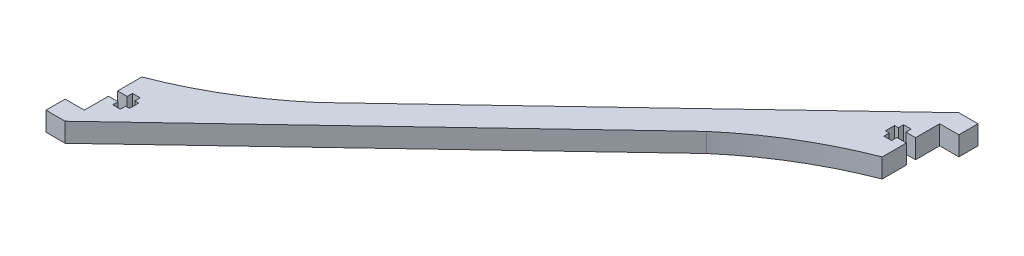
SolidWorks part; units mm, degrees
material "6061 Alloy"
ref_plane "Front Plane" through (0, 0, 0) normal (0, 0, 1) x (1, 0, 0)
ref_plane "Top Plane" through (0, 0, 0) normal (0, 1, 0) x (1, 0, 0)
ref_plane "Right Plane" through (0, 0, 0) normal (1, 0, 0) x (0, 0, -1)
sketch "Sketch1" plane through (0, 0, 0) normal (0, 1, 0) x (1, 0, 0)
  line L0 (1.2481, -4.6758) -> (2.4974, -4.6758)
  line L1 (2.4974, -4.6758) -> (2.4974, -2.9232)
  line L2 (2.4974, -2.9232) -> (5.0374, -2.9232)
  line L3 (5.0374, -2.9232) -> (5.0374, -4.6758)
  line L4 (5.0374, -4.6758) -> (8.2124, -4.6758)
  line L5 (8.2124, -4.6758) -> (8.2124, -3.0247)
  line L6 (8.2124, -3.0247) -> (8.2124, 3.3253)
  line L7 (1.2481, -7.7237) -> (2.4974, -7.7237)
  line L8 (2.4974, -7.7237) -> (2.4974, -9.4763)
  line L9 (2.4974, -9.4763) -> (5.0374, -9.4763)
  line L10 (5.0374, -9.4763) -> (5.0374, -7.7237)
  line L11 (5.0374, -7.7237) -> (8.2124, -7.7237)
  line L12 (8.2124, -7.7237) -> (8.2124, -15.7247)
  line L13 (-28.2056, -37.4925) -> (-137.4598, -140.8959)
  line L14 (-137.4598, -140.8959) -> (-143.8098, -140.8959)
  line L15 (-143.8098, -140.8959) -> (-143.8098, -134.5459)
  line L16 (-143.8098, -134.5459) -> (-137.4598, -134.5459)
  line L17 (-137.4598, -134.5459) -> (-137.4598, -126.5448)
  line L18 (-137.4598, -126.5448) -> (-134.2848, -126.5448)
  line L19 (-134.2848, -126.5448) -> (-134.2848, -128.2974)
  line L20 (-134.2848, -128.2974) -> (-131.7448, -128.2974)
  line L21 (-131.7448, -128.2974) -> (-131.7448, -126.5448)
  line L22 (-131.7448, -126.5448) -> (-130.4748, -126.5448)
  line L23 (-130.4748, -123.4969) -> (-131.7448, -123.4969)
  line L24 (-131.7448, -123.4969) -> (-131.7448, -121.7443)
  line L25 (-131.7448, -121.7443) -> (-134.2848, -121.7443)
  line L26 (-134.2848, -121.7443) -> (-134.2848, -123.4969)
  line L27 (-134.2848, -123.4969) -> (-137.4598, -123.4969)
  line L28 (-137.4598, -123.4969) -> (-137.4598, -115.4959)
  line L29 (-101.0417, -93.7281) -> (8.2124, 9.6753)
  line L30 (8.2124, 9.6753) -> (14.5624, 9.6753)
  line L31 (14.5624, 9.6753) -> (14.5624, 3.3253)
  line L32 (14.5624, 3.3253) -> (8.2124, 3.3253)
  line L33 (-130.4748, -123.4969) -> (-130.4748, -126.5448)
  line L34 (1.2481, -4.6758) -> (1.2481, -7.7237)
  arc A0 (8.2124, -15.7247) -> (-28.2056, -37.4925) centre (53.9573, -133.6051) ccw
  arc A1 (-137.4598, -115.4959) -> (-101.0417, -93.7281) centre (-183.2047, 2.3844) ccw
extrude "Boss-Extrude1" add sketch "Sketch1" along normal blind 6.35
